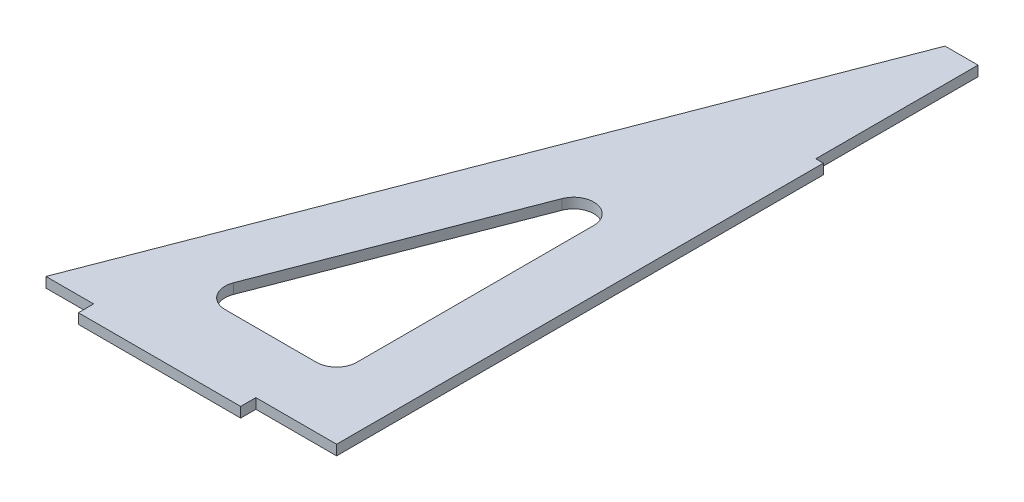
SolidWorks part; units mm, degrees
material "Balsa"
ref_plane "Front Plane" through (0, 0, 0) normal (0, 0, 1) x (1, 0, 0)
ref_plane "Top Plane" through (0, 0, 0) normal (0, 1, 0) x (1, 0, 0)
ref_plane "Right Plane" through (0, 0, 0) normal (1, 0, 0) x (0, 0, -1)
sketch "Sketch2" plane through (0, 0, 0) normal (0, 1, 0) x (1, 0, 0)
  line L0 (0, 0) -> (-91.7142, 0) construction
  line L1 (0, 0) -> (0, 47.6981) construction
  line L2 (0, 0) -> (-90.9828, 0)
  line L3 (-90.9828, 0) -> (-12.7, 203.2)
  line L4 (-12.7, 203.2) -> (0, 203.2)
  line L5 (0, 203.2) -> (0, 0)
  dimension "D1" = 90.9828
  dimension "D2" = 203.2
  dimension "D3" = 12.7
extrude "Boss-Extrude1" add sketch "Sketch2" along normal blind 3.175
sketch "Sketch3" plane through (0, 3.175, 0) normal (0, 1, 0) x (1, 0, 0)
  line L12 (-19.05, 19.05) -> (-19.05, 133.7262)
  line L13 (-19.05, 133.7262) -> (-63.229, 19.05)
  line L14 (-63.229, 19.05) -> (-19.05, 19.05)
  line L15 (-19.05, 19.05) -> (-19.05, 133.7262)
  line L16 (-19.05, 133.7262) -> (-63.229, 19.05)
  line L17 (-63.229, 19.05) -> (-19.05, 19.05)
  dimension "D1" = 19.05
extrude "Cut-Extrude2" cut sketch "Sketch3" against normal blind 3.175
fillet "Fillet2" radius 6.35 3 edges at (-19.05, 1.5875, -133.7262) (-19.05, 1.5875, -19.05) (-63.229, 1.5875, -19.05)
sketch "Sketch5" plane through (0, 0, 0) normal (0, 0, 1) x (1, 0, 0)
  line L0 (-90.9828, 3.175) -> (-90.9828, 0) construction
  line L1 (-90.9828, 3.175) -> (0, 3.175) construction
  line L4 (-76.073, 0) -> (-25.273, 0)
  line L5 (-76.073, 0) -> (-76.073, 3.175)
  line L6 (-76.073, 3.175) -> (-25.273, 3.175)
  line L7 (-25.273, 0) -> (-25.273, 3.175)
  line L8 (-76.073, 0) -> (-25.273, 3.175) construction
  line L9 (-76.073, 3.175) -> (-25.273, 0) construction
  point P0 (-50.673, 1.5875)
  point P11 (0, 0)
  dimension "D1" = 50.8
  dimension "D2" = 40.3098
  dimension "D3" = 3.175
extrude "Boss-Extrude2" add sketch "Sketch5" along normal blind 4.7625
sketch "Sketch6" plane through (0, 3.175, 0) normal (0, 1, 0) x (1, 0, 0)
  line L1 (0, 203.2) -> (-2.3813, 203.2)
  line L2 (0, 203.2) -> (0, 152.4)
  line L3 (0, 152.4) -> (-2.3812, 152.4)
  line L4 (-2.3813, 203.2) -> (-2.3812, 152.4)
  dimension "D1" = 50.8
  dimension "D2" = 2.3813
extrude "Cut-Extrude3" cut sketch "Sketch6" against normal through all
